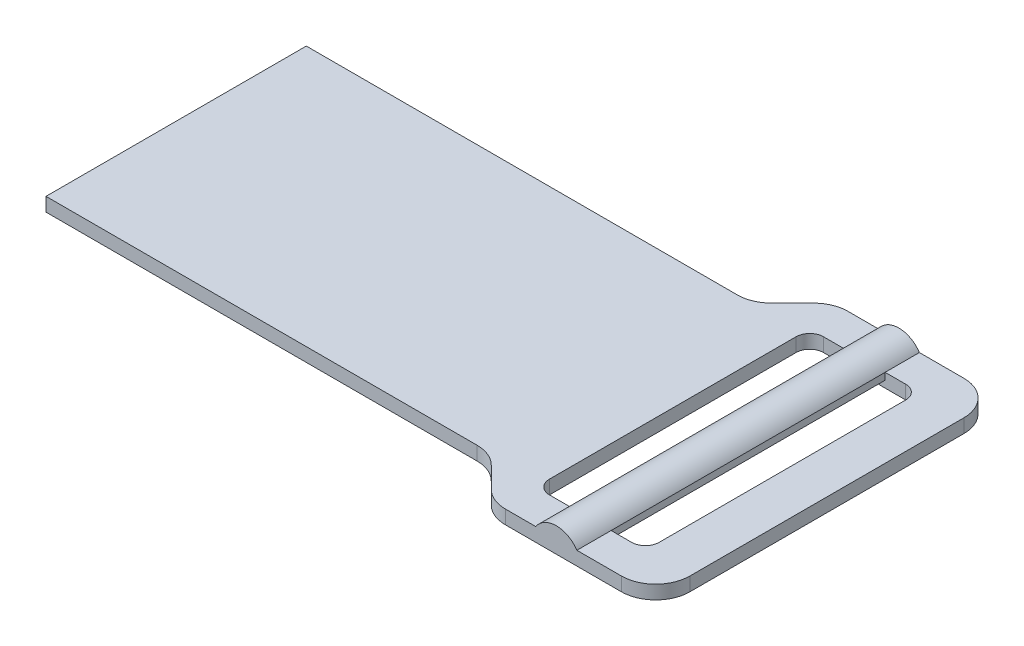
SolidWorks part; units mm, degrees
material "ABS"
ref_plane "Front Plane" through (0, 0, 0) normal (0, 0, 1) x (1, 0, 0)
ref_plane "Top Plane" through (0, 0, 0) normal (0, 1, 0) x (1, 0, 0)
ref_plane "Right Plane" through (0, 0, 0) normal (1, 0, 0) x (0, 0, -1)
sketch "Sketch1" plane through (0, 0, 0) normal (0, 1, 0) x (1, 0, 0)
  line L0 (32.5, -19) -> (38.5, -25)
  line L1 (-32.5, 19) -> (32.5, 19)
  line L2 (-32.5, 19) -> (-32.5, -19)
  line L3 (-32.5, -19) -> (32.5, -19)
  line L4 (32.5, 19) -> (32.5, -19) construction
  line L5 (-32.5, 19) -> (32.5, -19) construction
  line L6 (-32.5, -19) -> (32.5, 19) construction
  line L7 (38.5, -25) -> (62.5, -25)
  line L8 (62.5, -25) -> (62.5, 25)
  line L9 (62.5, 25) -> (38.5, 25)
  line L10 (38.5, 25) -> (32.5, 19)
  line L12 (56, -20) -> (40, -20)
  line L13 (56, -20) -> (56, 20)
  line L14 (56, 20) -> (40, 20)
  line L15 (40, -20) -> (40, 20)
  line L16 (56, -20) -> (40, 20) construction
  line L17 (56, 20) -> (40, -20) construction
  point P0 (0, 0)
  point P9 (62.5, 0)
  point P11 (48, 0)
  point P16 (0, 0)
  dimension "D1" = 65
  dimension "D2" = 38
  dimension "D3" = 30
  dimension "D4" = 50
  dimension "D5" = 24
  dimension "D6" = 48
  dimension "D7" = 16
  dimension "D8" = 40
extrude "Boss-Extrude1" add sketch "Sketch1" along normal blind 2
fillet "Fillet1" radius 5 6 edges at (32.5, 1, 19) (38.5, 1, 25) (32.5, 1, -19) (38.5, 1, -25) (62.5, 1, -25) (62.5, 1, 25)
fillet "Fillet2" radius 2 4 edges at (56, 1, 20) (56, 1, -20) (40, 1, 20) (40, 1, -20)
sketch "Sketch2" plane through (0, 0, 0) normal (0, 0, 1) x (1, 0, 0)
  line L0 (46, 0) -> (50, 0)
  line L1 (50, 0) -> (51, 1)
  line L2 (51, 1) -> (51, 2)
  line L3 (46, 0) -> (45, 1)
  line L4 (45, 1) -> (45, 2)
  arc A0 (51, 2) -> (45, 2) centre (48, 0) ccw
  point P3 (0, 0)
  dimension "D1" = 6
  dimension "D2" = 1
  dimension "D3" = 2
extrude "Boss-Extrude2" add sketch "Sketch2" along normal mid plane 50
